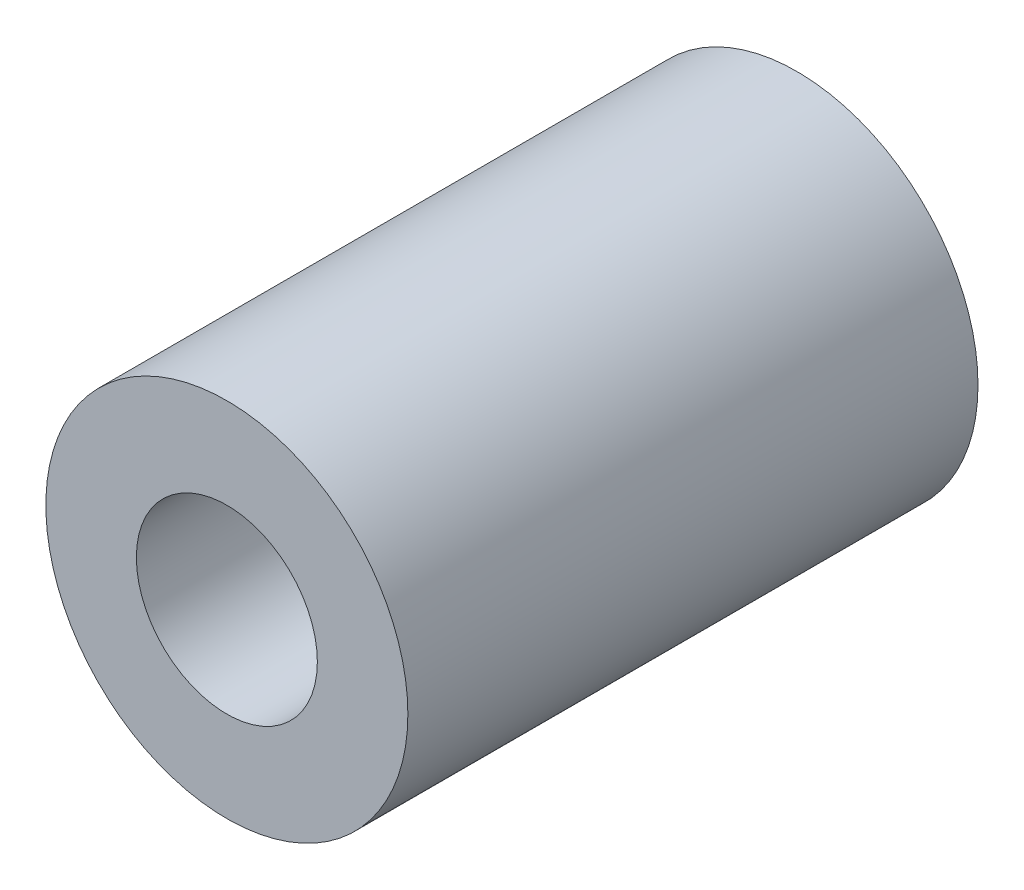
SolidWorks part; units mm, degrees
ref_plane "Front Plane" through (0, 0, 0) normal (0, 0, 1) x (1, 0, 0)
ref_plane "Top Plane" through (0, 0, 0) normal (0, 1, 0) x (1, 0, 0)
ref_plane "Right Plane" through (0, 0, 0) normal (1, 0, 0) x (0, 0, -1)
sketch "Sketch1" plane through (0, 0, 0) normal (0, 0, 1) x (1, 0, 0)
  circle A0 centre (0, 0) radius 1.5875
  circle A1 centre (0, 0) radius 3.175
  dimension "D1" = 6.35
  dimension "D2" = 3.175
extrude "Boss-Extrude1" add sketch "Sketch1" along normal blind 10
